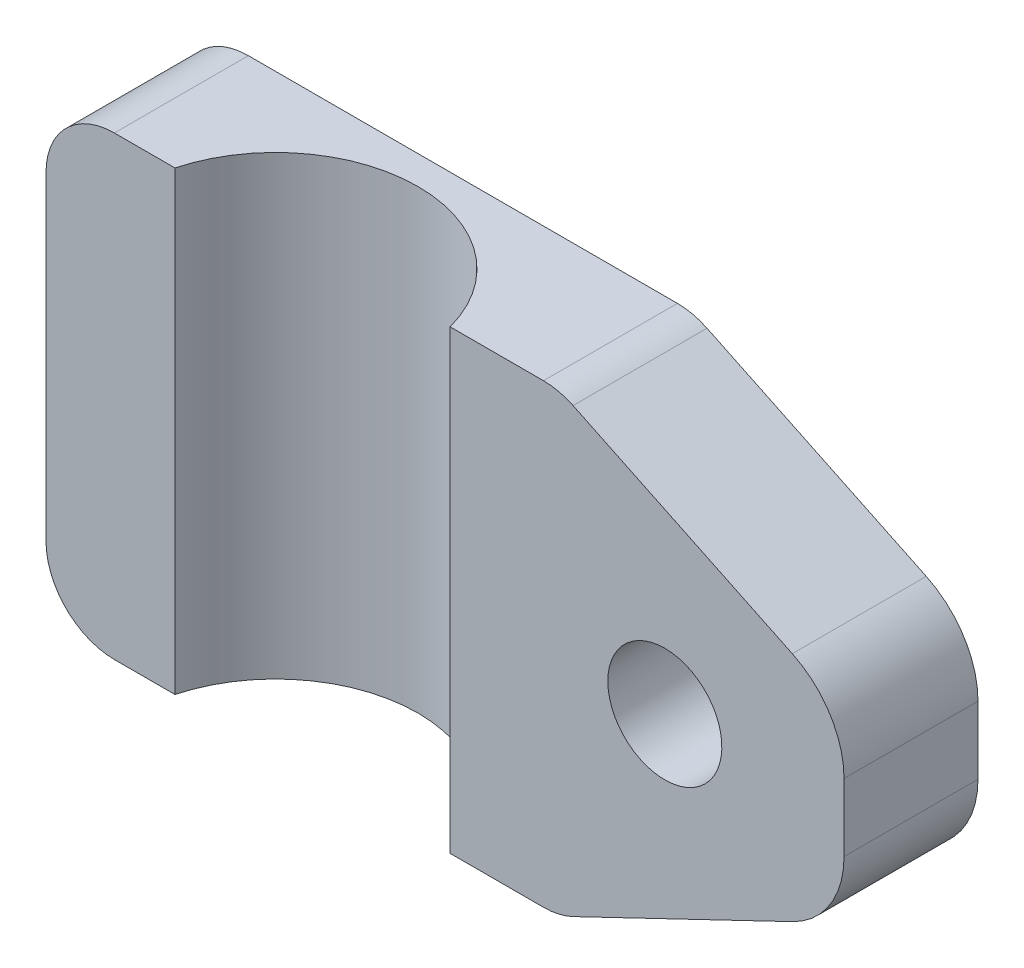
SolidWorks part; units mm, degrees
ref_plane "Front Plane" through (0, 0, 0) normal (0, 0, 1) x (1, 0, 0)
ref_plane "Top Plane" through (0, 0, 0) normal (0, 1, 0) x (1, 0, 0)
ref_plane "Right Plane" through (0, 0, 0) normal (1, 0, 0) x (0, 0, -1)
sketch "Sketch1" plane through (0, 0, 0) normal (0, 0, 1) x (1, 0, 0)
  line L0 (-35, 0) -> (35, 0) construction
  line L1 (-35, -14) -> (-35, 14)
  line L2 (-29, 20) -> (8.6346, 20)
  line L3 (11.231, 19.4091) -> (30.4618, 10.1783)
  line L4 (35, 2.9661) -> (35, -2.9661)
  line L5 (11.231, -19.4091) -> (30.4618, -10.1783)
  line L6 (-29, -20) -> (8.6346, -20)
  arc A0 (8.6346, 20) -> (11.231, 19.4091) centre (8.6346, 14) cw
  arc A1 (-35, 14) -> (-29, 20) centre (-29, 14) cw
  arc A2 (30.4618, 10.1783) -> (35, 2.9661) centre (27, 2.9661) cw
  arc A3 (30.4618, -10.1783) -> (35, -2.9661) centre (27, -2.9661) ccw
  arc A4 (-35, -14) -> (-29, -20) centre (-29, -14) ccw
  arc A5 (8.6346, -20) -> (11.231, -19.4091) centre (8.6346, -14) ccw
  point P4 (0, 0)
  point P10 (10, 20)
  point P13 (-35, 20)
  point P16 (35, 8)
  point P18 (35, 0)
  point P26 (35, -8)
  point P27 (-35, -20)
  point P28 (10, -20)
  dimension "D5" = 6
  dimension "D6" = 8
  dimension "D7" = 35
  dimension "D1" = 20
  dimension "D2" = 45
  dimension "D3" = 70
  dimension "D4" = 8
extrude "Boss-Extrude1" add sketch "Sketch1" along normal blind 25
sketch "Sketch3" plane through (0, -20, 0) normal (0, -1, 0) x (-1, 0, 0)
  line L0 (35, -25) -> (24.12, -25)
  line L1 (29, -25) -> (-8.6346, -25) construction
  line L2 (-0.88, -25) -> (-35, -25)
  line L3 (-35, -25) -> (-35, -10)
  line L4 (-35, -25) -> (-35, 0) construction
  line L5 (35, -10) -> (-35, -10)
  line L6 (35, -25) -> (35, -10)
  line L7 (35, -25) -> (35, 0) construction
  arc A0 (24.12, -25) -> (-0.88, -25) centre (11.62, -25) ccw
  arc A1 (26.62, -25) -> (-3.38, -25) centre (11.62, -25) ccw
  line M7 (29, 0) -> (-8.6346, 0)
  line M8 (-8.6346, 0) -> (-8.6346, -25)
  line M9 (-8.6346, -25) -> (29, -25)
  line M10 (29, -25) -> (29, 0)
  dimension "D2" = 12.5
  dimension "D4" = 30
  dimension "D1" = 15
  dimension "D3" = 15
extrude "Cut-Extrude2" cut sketch "Sketch3" against normal through all contours A0 M9 | L5 M10 M7 M8
sketch "Sketch4" plane through (8.6346, 0, 0) normal (-1, 0, 0) x (0, 0, 1)
  line L4 (0, -20) -> (10, -20)
  line L5 (10, -20) -> (10, 20)
  line L6 (10, 20) -> (0, 20)
  line L7 (0, 20) -> (0, -20)
  line L8 (0, -20) -> (10, -20)
  line L9 (10, -20) -> (10, 20)
  line L10 (10, 20) -> (0, 20)
  line L11 (0, 20) -> (0, -20)
  dimension "D1" = 0
extrude "Cut-Extrude3" cut sketch "Sketch4" against normal mid plane 115
sketch "Sketch5" plane through (0, 0, 10) normal (0, 0, -1) x (-1, 0, 0)
  line L0 (-8.6346, 11) -> (-8.6346, -11)
  line L1 (29, 20) -> (-8.6346, 20) construction
  line L2 (29, 20) -> (-8.6346, 20)
  line L9 (-8.6346, -20) -> (29, -20)
  line L10 (35, -14) -> (35, 14)
  line L11 (29, 20) -> (-8.6346, 20)
  line L12 (-11.231, 19.4091) -> (-30.4618, 10.1783)
  line L13 (-35, 2.9661) -> (-35, -2.9661)
  line L14 (-30.4618, -10.1783) -> (-11.231, -19.4091)
  line L15 (-8.6346, -20) -> (29, -20)
  line L16 (35, -14) -> (35, 14)
  line L17 (29, 20) -> (-8.6346, 20)
  line L21 (-2.6346, -14) -> (26, -14)
  line L22 (29, -11) -> (29, 11)
  line L23 (26, 14) -> (-2.6346, 14)
  line L24 (-5.6346, 11) -> (-5.6346, -11)
  line L27 (-8.6346, -17) -> (29, -17)
  line L28 (32, -14) -> (32, 14)
  line L29 (29, 17) -> (-8.6346, 17)
  line L30 (-9.9328, 16.7046) -> (-29.1637, 7.4737)
  line L31 (-32, 2.9661) -> (-32, -2.9661)
  line L32 (-29.1637, -7.4737) -> (-9.9328, -16.7046)
  line L33 (-2.6346, -17) -> (26, -17)
  line L34 (32, -11) -> (32, 11)
  line L35 (26, 17) -> (-2.6346, 17)
  arc A6 (29, -20) -> (35, -14) centre (29, -14) ccw
  arc A7 (35, 14) -> (29, 20) centre (29, 14) ccw
  arc A8 (-8.6346, 20) -> (-11.231, 19.4091) centre (-8.6346, 14) ccw
  arc A9 (-30.4618, 10.1783) -> (-35, 2.9661) centre (-27, 2.9661) ccw
  arc A10 (-35, -2.9661) -> (-30.4618, -10.1783) centre (-27, -2.9661) ccw
  arc A11 (-11.231, -19.4091) -> (-8.6346, -20) centre (-8.6346, -14) ccw
  arc A12 (29, -20) -> (35, -14) centre (29, -14) ccw
  arc A13 (35, 14) -> (29, 20) centre (29, 14) ccw
  arc A18 (26, 17) -> (32, 11) centre (26, 11) cw
  arc A19 (32, -11) -> (26, -17) centre (26, -11) cw
  arc A20 (-8.6346, 11) -> (-2.6346, 17) centre (-2.6346, 11) cw
  arc A21 (-2.6346, -17) -> (-8.6346, -11) centre (-2.6346, -11) cw
  arc A22 (29, -11) -> (26, -14) centre (26, -11) cw
  arc A23 (26, 14) -> (29, 11) centre (26, 11) cw
  arc A24 (29, -17) -> (32, -14) centre (29, -14) ccw
  arc A25 (32, 14) -> (29, 17) centre (29, 14) ccw
  arc A26 (-8.6346, 17) -> (-9.9328, 16.7046) centre (-8.6346, 14) ccw
  arc A27 (-29.1637, 7.4737) -> (-32, 2.9661) centre (-27, 2.9661) ccw
  arc A28 (-32, -2.9661) -> (-29.1637, -7.4737) centre (-27, -2.9661) ccw
  arc A29 (-9.9328, -16.7046) -> (-8.6346, -17) centre (-8.6346, -14) ccw
  arc A30 (29, -17) -> (32, -14) centre (29, -14) ccw
  arc A31 (32, 14) -> (29, 17) centre (29, 14) ccw
  arc A36 (-5.6346, 11) -> (-2.6346, 14) centre (-2.6346, 11) cw
  arc A37 (-2.6346, -14) -> (-5.6346, -11) centre (-2.6346, -11) cw
  dimension "D3" = 6
  dimension "D1" = 0
  dimension "D2" = 3
  dimension "D4" = 3
extrude "Cut-Extrude4" cut sketch "Sketch5" against normal blind 1 contours L24 A37 L21 A22 L22 A23 L23 A36
sketch "Sketch6" plane through (0, 0, 10) normal (0, 0, -1) x (-1, 0, 0)
  line L0 (-11.231, 19.4091) -> (-11.231, -19.4091) construction
  circle A0 centre (-19.281, 0) radius 5
  dimension "D1" = 10
  dimension "D2" = 8.05
extrude "Cut-Extrude5" cut sketch "Sketch6" against normal through all
sketch "Sketch9" plane through (-35, 0, 0) normal (-1, 0, 0) x (0, 0, 1)
  line L0 (25, 20) -> (21.75, 20)
  line L1 (25, 20) -> (10, 20) construction
  line L2 (21.75, 20) -> (21.75, -20)
  line L3 (25, -20) -> (10, -20) construction
  line L4 (21.75, -20) -> (25, -20)
  line L5 (25, -20) -> (25, 20)
  dimension "D1" = 3.25
extrude "Cut-Extrude6" cut sketch "Sketch9" against normal through all
